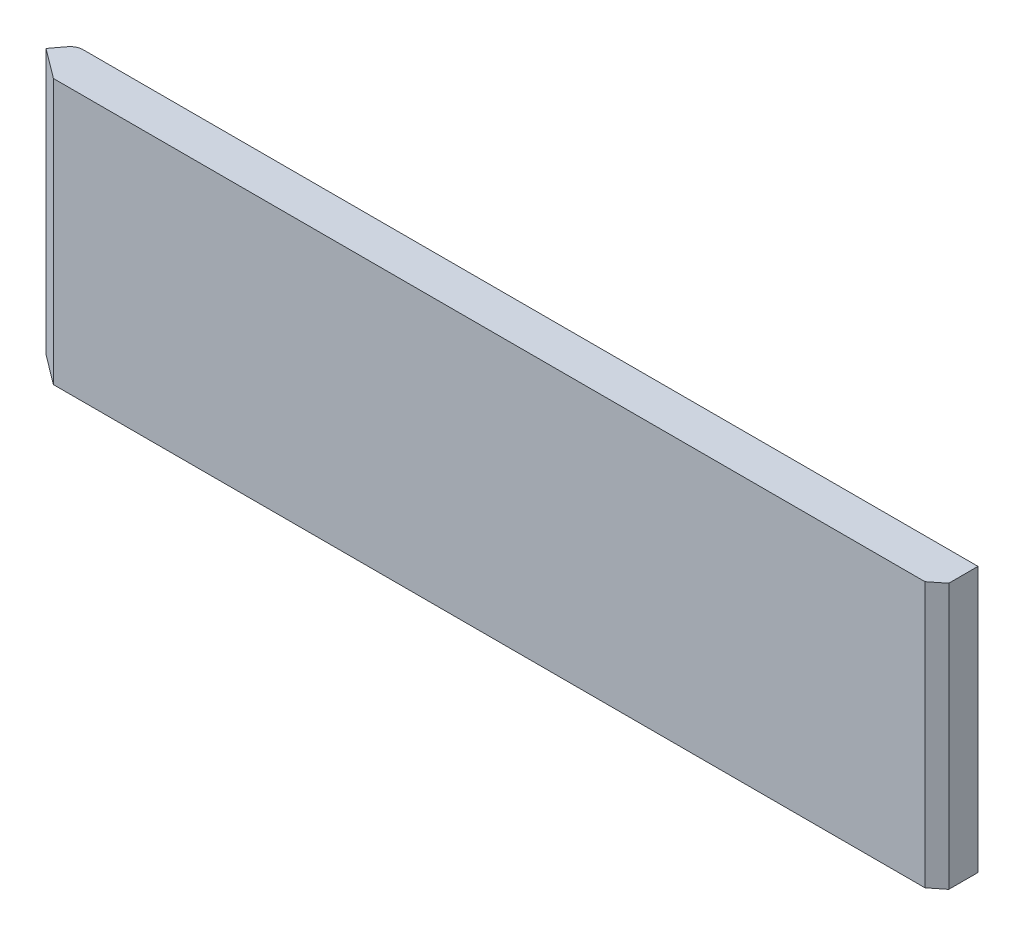
SolidWorks part; units mm, degrees
ref_plane "Front Plane" through (0, 0, 0) normal (0, 0, 1) x (1, 0, 0)
ref_plane "Top Plane" through (0, 0, 0) normal (0, 1, 0) x (1, 0, 0)
ref_plane "Right Plane" through (0, 0, 0) normal (1, 0, 0) x (0, 0, -1)
sketch "Sketch1" plane through (0, 0, 0) normal (0, 1, 0) x (1, 0, 0)
  line L0 (-110, 0) -> (-80, 40)
  line L1 (-80, 40) -> (80, 40)
  line L3 (77.5, 34) -> (-77.5, 34)
  line L4 (-77.5, 34) -> (-103, 0)
  line L5 (-103, 0) -> (-110, 0)
  line L6 (0, -55) -> (0, 55) construction
  line L7 (103, 0) -> (110, 0)
  line L8 (77.5, 34) -> (103, 0)
  line L9 (110, 0) -> (80, 40)
  dimension "D1" = 6
  dimension "D2" = 7
  dimension "D3" = 40
  dimension "D4" = 30
extrude "Boss-Extrude1" add sketch "Sketch1" along normal mid plane 40
sketch "Sketch2" plane through (0, 20, 0) normal (0, 1, 0) x (1, 0, 0)
  line L1 (-80, 40) -> (-110, 0) construction
  line L2 (80, 40) -> (-80, 40) construction
  line L3 (0, -22) -> (0, 22) construction
  circle A0 centre (-104, 3) radius 1.5
  circle A1 centre (-57, 37) radius 1.5
  circle A2 centre (-7, 37) radius 1.5
  circle A3 centre (7, 37) radius 1.5
  circle A5 centre (104, 3) radius 1.5
  circle A6 centre (52, 37) radius 1.5725
  dimension "D2" = 3
  dimension "D3" = 3
  dimension "D5" = 3
  dimension "D1" = 50
  dimension "D4" = 7
  dimension "D6" = 3
  dimension "D7" = 3
  dimension "D8" = 3
  dimension "D9" = 37
  dimension "D10" = 45
extrude "Cut-Extrude1" cut sketch "Sketch2" against normal blind 5 from offset 35 offset against normal yes
fillet "Fillet1" radius 2 2 edges at (80, 0, -40) (-80, 0, -40)
sketch "Sketch3" plane through (-65.92, 0, -49.44) normal (0.8, 0, 0.6) x (0.6, 0, -0.8)
  line L1 (-19.3, -20) -> (-123.0845, -20)
  line L2 (-19.3, -20) -> (-19.3, 53.7488)
  line L3 (-19.3, 53.7488) -> (-123.0845, 53.7488)
  line L4 (-123.0845, -20) -> (-123.0845, 53.7488)
extrude "Cut-Extrude2" cut sketch "Sketch3" against normal through all both and the other way through all
mirror "Mirror1" about plane through (0, 0, 0) normal (1, 0, 0) of "Cut-Extrude2"
sketch "Sketch4" plane through (0, 0, -34) normal (0, 0, 1) x (1, 0, 0)
  line L0 (-77.5, 20) -> (77.5, 20) construction
  line L1 (81.98, -20) -> (55.98, -20)
  line L2 (81.98, -20) -> (81.98, 20)
  line L3 (81.98, 20) -> (55.98, 20)
  line L4 (55.98, -20) -> (55.98, 20)
  dimension "D1" = 26
extrude "Cut-Extrude3" cut sketch "Sketch4" against normal through all both and the other way through all
sketch "Sketch5" plane through (0, -20, 0) normal (0, -1, 0) x (1, 0, 0)
  line L0 (55.98, -35.588) -> (53.98, -34)
  line L1 (55.98, -40) -> (55.98, -34) construction
  line L2 (-77.5, -34) -> (55.98, -34) construction
  line L3 (53.98, -34) -> (55.98, -34)
  line L4 (55.98, -34) -> (55.98, -35.588)
  dimension "D1" = 38.45
  dimension "D3" = 2
extrude "Cut-Extrude4" cut sketch "Sketch5" against normal through all both and the other way through all
